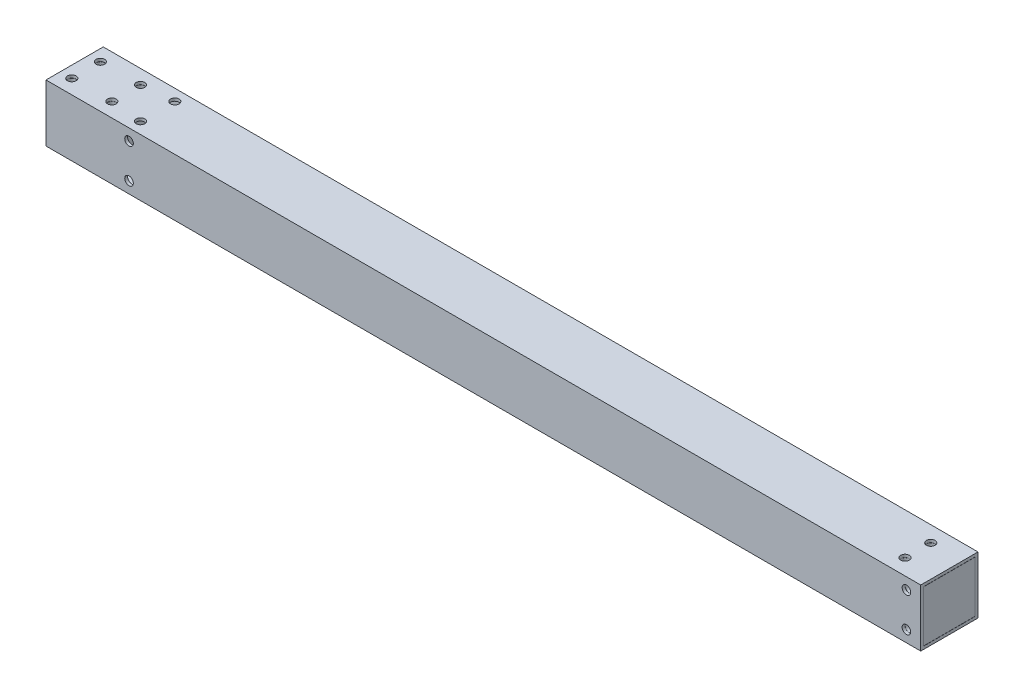
SolidWorks part; units mm, degrees
ref_plane "Front" through (0, 0, 0) normal (0, 0, 1) x (1, 0, 0)
ref_plane "Top" through (0, 0, 0) normal (0, 1, 0) x (1, 0, 0)
ref_plane "Right" through (0, 0, 0) normal (1, 0, 0) x (0, 0, -1)
sketch "草图1" plane through (0, 0, 0) normal (0, 1, 0) x (1, 0, 0)
  line L0 (0, 0) -> (305.54, 0)
  dimension "D1" = 305.54
other "铝管 20X20X1(1)"
ref_plane "基准面1" through (0, 0, 0) normal (1, 0, 0) x (0, 0, -1)
sketch "草图11" plane through (0, 0, 0) normal (1, 0, 0) x (0, 0, -1)
  line L1 (-10, -10) -> (10, -10)
  line L2 (-10, -10) -> (-10, 10)
  line L3 (-10, 10) -> (10, 10)
  line L4 (10, -10) -> (10, 10)
  line L5 (-10, -10) -> (10, 10) construction
  line L6 (-10, 10) -> (10, -10) construction
  line L7 (-9, -9) -> (9, -9)
  line L8 (-9, -9) -> (-9, 9)
  line L9 (-9, 9) -> (9, 9)
  line L10 (9, -9) -> (9, 9)
  line L11 (-9, -9) -> (9, 9) construction
  line L12 (-9, 9) -> (9, -9) construction
  point P0 (0, 0)
  point P6 (0, 0)
  point P11 (0, 0)
  dimension "D1" = 20
  dimension "D2" = 20
  dimension "D3" = 18
  dimension "D4" = 18
sketch "草图12" plane through (305.54, 0, 0) normal (1, 0, 0) x (0, 0, -1)
  line L1 (8.95, -8.95) -> (-8.95, -8.95)
  line L2 (8.95, -8.95) -> (8.95, 8.95)
  line L3 (8.95, 8.95) -> (-8.95, 8.95)
  line L4 (-8.95, -8.95) -> (-8.95, 8.95)
  line L5 (8.95, -8.95) -> (-8.95, 8.95) construction
  line L6 (8.95, 8.95) -> (-8.95, -8.95) construction
  point P0 (0, 0)
  dimension "D1" = 17.9
extrude "凸台-拉伸1" add sketch "草图12" against normal blind 20 separate body
sketch "草图13" plane through (0, 0, 0) normal (-1, 0, 0) x (0, 0, 1)
  line L1 (8.95, -8.95) -> (-8.95, -8.95)
  line L2 (8.95, -8.95) -> (8.95, 8.95)
  line L3 (8.95, 8.95) -> (-8.95, 8.95)
  line L4 (-8.95, -8.95) -> (-8.95, 8.95)
  line L5 (8.95, -8.95) -> (-8.95, 8.95) construction
  line L6 (8.95, 8.95) -> (-8.95, -8.95) construction
  point P0 (0, 0)
  dimension "D1" = 17.9
extrude "凸台-拉伸2" add sketch "草图13" against normal blind 20 separate body
sketch "草图14" plane through (0, 10, 0) normal (0, 1, 0) x (1, 0, 0)
  line L0 (294.54, 10) -> (294.54, -10) construction
  line L1 (305.54, 10) -> (0, 10) construction
  line L2 (305.54, -10) -> (0, -10) construction
  line L3 (305.54, 10) -> (305.54, -10) construction
  circle A0 centre (294.54, 4.5) radius 1.5
  circle A1 centre (294.54, -4.5) radius 1.5
  dimension "D1" = 3
  dimension "D2" = 3
  dimension "D3" = 5.5
  dimension "D4" = 9
  dimension "D5" = 11
extrude "切除-拉伸1" cut sketch "草图14" against normal through all
sketch "草图15" plane through (0, 10, 0) normal (0, 1, 0) x (1, 0, 0)
  line L0 (0, 0) -> (57.4874, 0) construction
  line L1 (0, 10) -> (0, -10) construction
  line L2 (305.54, 10) -> (0, 10) construction
  circle A0 centre (4, 5) radius 1.5
  circle A1 centre (4, -5) radius 1.5
  circle A2 centre (18, 5) radius 1.5
  circle A3 centre (18, -5) radius 1.5
  dimension "D1" = 3
  dimension "D2" = 3
  dimension "D3" = 4
  dimension "D4" = 5
  dimension "D5" = 10
  dimension "D7" = 14
  dimension "D6" = 2
extrude "切除-拉伸2" cut sketch "草图15" against normal through all
sketch "草图16" plane through (0, 0, 10) normal (0, 0, -1) x (1, 0, 0)
  line L0 (0, 10) -> (0, -10) construction
  line L1 (305.54, -10) -> (0, -10) construction
  circle A0 centre (29, -6) radius 1.5
  circle A1 centre (29, 6) radius 1.5
  dimension "D1" = 3
  dimension "D4" = 3
  dimension "D2" = 4
  dimension "D3" = 29
  dimension "D5" = 12
extrude "切除-拉伸3" cut sketch "草图16" along normal through all
sketch "草图17" plane through (0, 0, -10) normal (0, 0, -1) x (-1, 0, 0)
  line L0 (-300.54, 10) -> (-300.54, -10) construction
  line L1 (-305.54, 10) -> (0, 10) construction
  line L2 (-305.54, -10) -> (0, -10) construction
  line L3 (-305.54, -10) -> (-305.54, 10) construction
  circle A0 centre (-300.54, 6) radius 1.5
  circle A1 centre (-300.54, -6) radius 1.5
  dimension "D1" = 3
  dimension "D2" = 3
  dimension "D3" = 4
  dimension "D4" = 4
  dimension "D5" = 5
extrude "切除-拉伸4" cut sketch "草图17" against normal through all
sketch "草图18" plane through (0, 10, 0) normal (0, 1, 0) x (1, 0, 0)
  line L0 (29, 10) -> (29, -10) construction
  line L1 (305.54, 10) -> (0, 10) construction
  line L2 (305.54, -10) -> (0, -10) construction
  line L3 (0, 10) -> (0, -10) construction
  circle A0 centre (29, 6) radius 1.5
  circle A1 centre (29, -6) radius 1.5
  dimension "D2" = 3
  dimension "D3" = 3
  dimension "D1" = 29
  dimension "D4" = 4
  dimension "D5" = 12
extrude "切除-拉伸5" cut sketch "草图18" against normal through all
